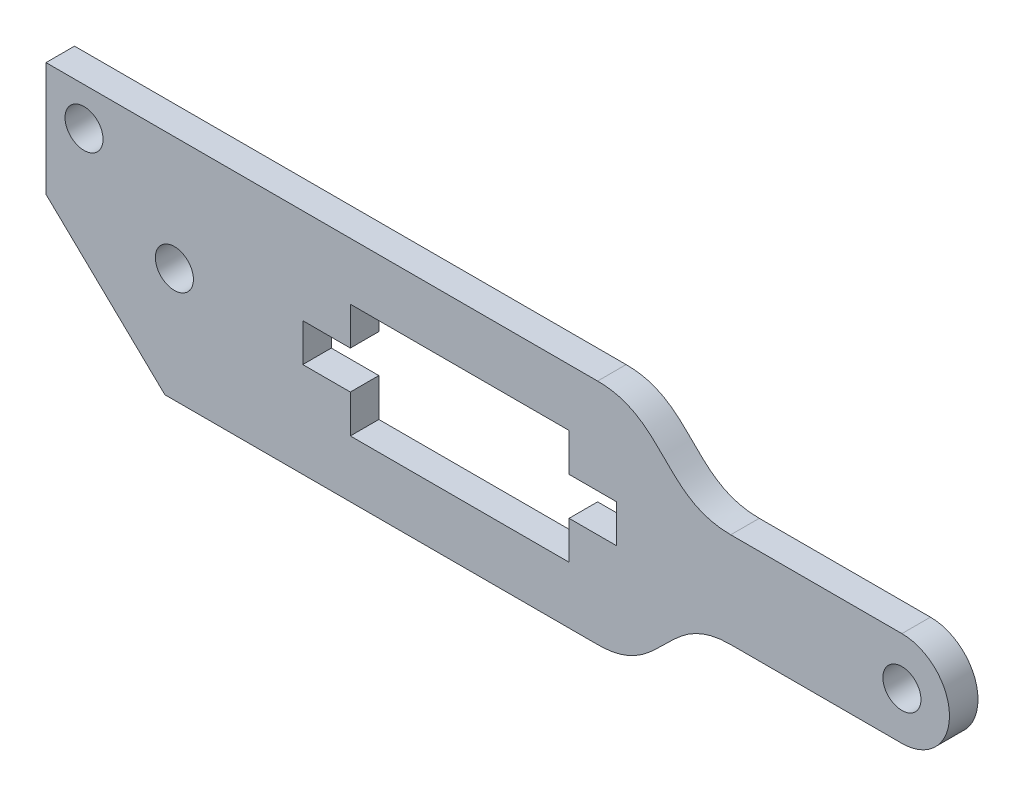
SolidWorks part; units mm, degrees
ref_plane "Plan de face" through (0, 0, 0) normal (0, 0, 1) x (1, 0, 0)
ref_plane "Plan de dessus" through (0, 0, 0) normal (0, 1, 0) x (1, 0, 0)
ref_plane "Plan de droite" through (0, 0, 0) normal (1, 0, 0) x (0, 0, -1)
sketch "Esquisse1" plane through (0, 0, 0) normal (0, 0, 1) x (1, 0, 0)
  line L0 (-47.5, 0) -> (-35, -12)
  line L1 (47.5, -12) -> (-47.5, -12)
  line L2 (47.5, -12) -> (47.5, 12)
  line L3 (47.5, 12) -> (-47.5, 12)
  line L4 (-47.5, -12) -> (-47.5, 12)
  line L5 (47.5, -12) -> (-47.5, 12) construction
  line L6 (47.5, 12) -> (-47.5, -12) construction
  line L7 (24.5, 5) -> (17.5, 5) construction
  line L8 (47.5, -12) -> (17.5, -12)
  line L9 (47.5, -12) -> (47.5, -5)
  line L10 (47.5, -5) -> (17.5, -5)
  line L11 (17.5, -12) -> (17.5, -5)
  line L12 (47.5, 5) -> (17.5, 5)
  line L13 (47.5, 5) -> (47.5, 12)
  line L14 (47.5, 12) -> (17.5, 12)
  line L15 (17.5, 5) -> (17.5, 12)
  line L16 (-15.5, 6) -> (7.5, 6)
  line L17 (-15.5, 6) -> (-15.5, -6)
  line L18 (-15.5, -6) -> (7.5, -6)
  line L19 (7.5, 6) -> (7.5, -6)
  line L20 (17.5, 5) -> (17.5, 12) construction
  line L21 (17.5, 12) -> (10.5, 12) construction
  line L22 (24.5, -5) -> (17.5, -5) construction
  line L23 (17.5, -5) -> (17.5, -12) construction
  line L24 (17.5, -12) -> (10.5, -12) construction
  line L25 (-47.5, 0) -> (-20.5, 0) construction
  line L26 (-15.5, 2) -> (-20.5, 2)
  line L27 (-15.5, 2) -> (-15.5, -2)
  line L28 (-15.5, -2) -> (-20.5, -2)
  line L29 (-20.5, 2) -> (-20.5, -2)
  line L30 (7.5, 2) -> (12.5, 2)
  line L31 (7.5, 2) -> (7.5, -2)
  line L32 (7.5, -2) -> (12.5, -2)
  line L33 (12.5, 2) -> (12.5, -2)
  circle A0 centre (42.5, 0) radius 2
  circle A1 centre (-34, 0) radius 2
  circle A2 centre (42.5, 0) radius 5
  circle A3 centre (-43.5, 8) radius 2
  spline S0 degree 3 poles (24.5, 5) (17.5, 5) (17.5, 12) (10.5, 12) knots 0 0 0 0 1 1 1 1
  spline S1 degree 3 poles (24.5, -5) (17.5, -5) (17.5, -12) (10.5, -12) knots 0 0 0 0 1 1 1 1
  point P0 (0, 0)
  point P42 (0, 0)
  point P44 (-45.8952, 9.1871)
  dimension "D12" = 7
  dimension "D13" = 4
  dimension "D20" = 4
  dimension "D23" = 4
  dimension "D1" = 24
  dimension "D2" = 95
  dimension "D3" = 30
  dimension "D4" = 7
  dimension "D5" = 30
  dimension "D6" = 7
  dimension "D7" = 23
  dimension "D8" = 12
  dimension "D9" = 6
  dimension "D10" = 10
  dimension "D11" = 7
  dimension "D14" = 4
  dimension "D15" = 4
  dimension "D16" = 5
  dimension "D17" = 4
  dimension "D18" = 4
  dimension "D19" = 5
  dimension "D21" = 4
  dimension "D22" = 4
extrude "Boss.-Extru.1" add sketch "Esquisse1" along normal blind 3 contours S1 L11 L10 A2 L12 L15 S0 L3 L4 L0 L1 L16 L19 L18 L17 | L12 S0 L15 | S1 L10 L11 | A2
